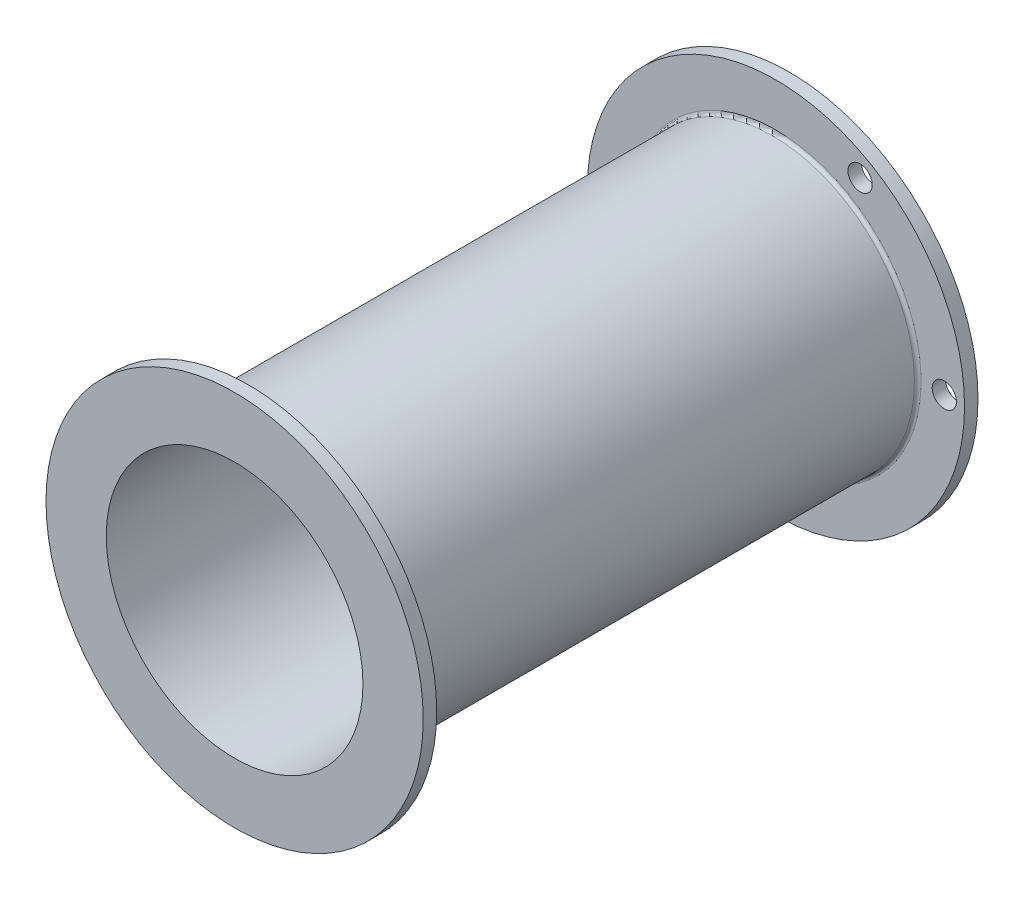
SolidWorks part; units mm, degrees
material "6061-T6 (SS)"
ref_plane "Front Plane" through (0, 0, 0) normal (0, 0, 1) x (1, 0, 0)
ref_plane "Top Plane" through (0, 0, 0) normal (0, 1, 0) x (1, 0, 0)
ref_plane "Right Plane" through (0, 0, 0) normal (1, 0, 0) x (0, 0, -1)
sketch "Sketch1" plane through (0, 0, 0) normal (0, 0, 1) x (1, 0, 0)
  circle A0 centre (0, 0) radius 9.525
  circle A1 centre (0, 0) radius 10.525
  dimension "D1" = 19.05
  dimension "D2" = 21.05
extrude "Boss-Extrude1" add sketch "Sketch1" along normal blind 40.18
sketch "Sketch2" plane through (0, 0, 0) normal (0, 0, -1) x (-1, 0, 0)
  circle A0 centre (0, 0) radius 14
  circle A1 centre (0, 0) radius 9.525 construction
  circle A2 centre (0, 0) radius 9.525
  dimension "D1" = 28
  dimension "D2" = 0
extrude "Boss-Extrude2" add sketch "Sketch2" along normal blind 1
hole_wizard "M1.6 Clearance Hole1" positions "Sketch10" profile "Sketch11" hole size "M1.6" standard "ISO"
sketch "Sketch10" plane through (0, 0, 0) normal (0, 0, 1) x (1, 0, 0)
  point P0 (-12.5, 0)
  dimension "D1" = 12.5
sketch "Sketch11" plane through (-12.5, 0, 0) normal (1, 0, 0) x (0, -1, 0)
  line L0 (0, 0) -> (0, 5.5408)
  line L1 (0, 5.5408) -> (0.9, 5)
  line L2 (0.9, 5) -> (0.9, 0)
  line L5 (0.9, 0) -> (0, 0)
  line L10 (0, 5.5408) -> (-0.9, 5) construction
  line L11 (0, -6.35) -> (0, 107.95) construction
  dimension "Hole Dia." = 1.8
  dimension "Hole Depth" = 5
  dimension "Drill Angle" = 118
pattern_circular "CirPattern1" count 6 over 360 about axis through (0, 0, 0) along (0, 0, -1) skipping 1, 4 of "M1.6 Clearance Hole1"
fillet "Fillet1" radius 0.25 1 edges at (10.525, 0, 0)
ref_plane "Plane1" through (0, 0, 19.59) normal (0, 0, 1) x (1, 0, 0)
mirror "Mirror1" about plane through (0, 0, 19.59) normal (0, 0, 1) of "Boss-Extrude2"
